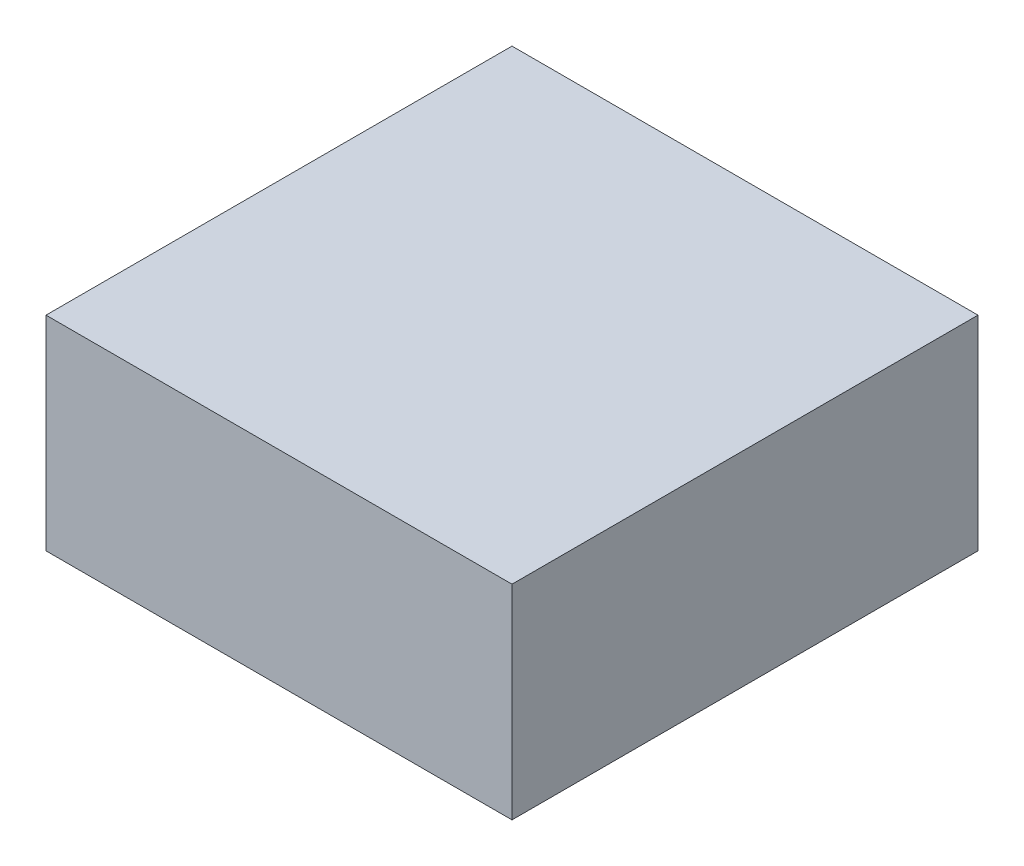
SolidWorks part; units mm, degrees
ref_plane "Front Plane" through (0, 0, 0) normal (0, 0, 1) x (1, 0, 0)
ref_plane "Top Plane" through (0, 0, 0) normal (0, 1, 0) x (1, 0, 0)
ref_plane "Right Plane" through (0, 0, 0) normal (1, 0, 0) x (0, 0, -1)
sketch "Sketch1" plane through (0, 0, 0) normal (0, 1, 0) x (1, 0, 0)
  line L1 (-105, 105) -> (105, 105)
  line L2 (-105, 105) -> (-105, -105)
  line L3 (-105, -105) -> (105, -105)
  line L4 (105, 105) -> (105, -105)
  line L5 (-105, 105) -> (105, -105) construction
  line L6 (-105, -105) -> (105, 105) construction
  point P0 (0, 0)
  dimension "D1" = 210
  dimension "D2" = 210
extrude "Boss-Extrude1" add sketch "Sketch1" along normal blind 92
equation "\"width\"=210"
equation "\"D1@Sketch1\"=\"width\""
equation "\"depth\"=210"
equation "\"D2@Sketch1\"=\"depth\""
equation "\"height\"= 100 - 8"
equation "\"D1@Boss-Extrude1\"=\"height\""
